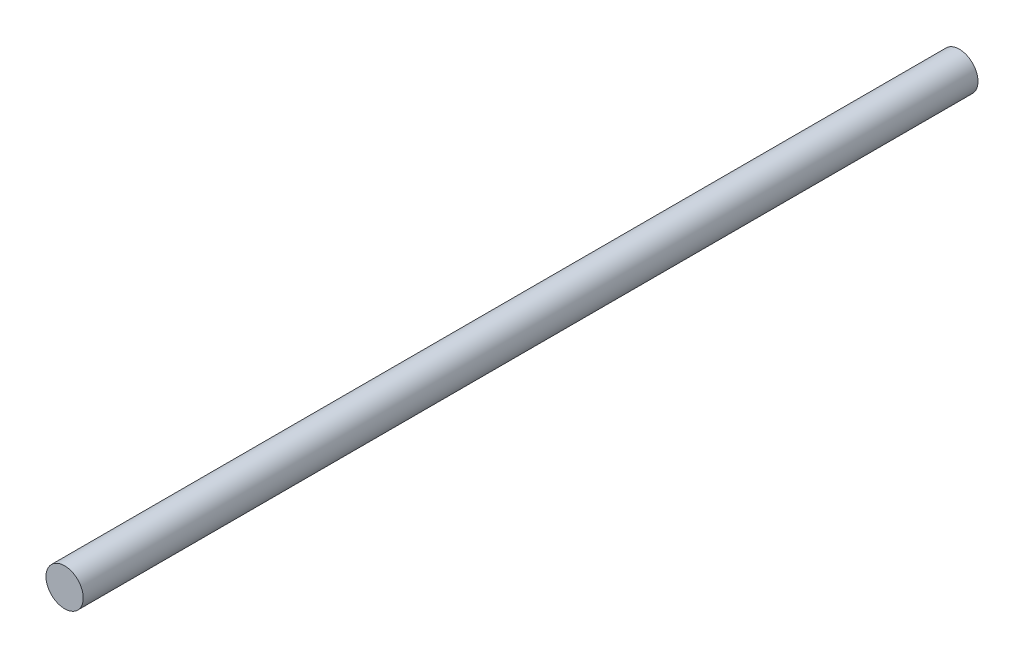
SolidWorks part; units mm, degrees
ref_plane "Front Plane" through (0, 0, 0) normal (0, 0, 1) x (1, 0, 0)
ref_plane "Top Plane" through (0, 0, 0) normal (0, 1, 0) x (1, 0, 0)
ref_plane "Right Plane" through (0, 0, 0) normal (1, 0, 0) x (0, 0, -1)
sketch "Sketch1" plane through (0, 0, 0) normal (0, 0, 1) x (1, 0, 0)
  circle A0 centre (0, 0) radius 2.5
  dimension "D1" = 5
extrude "Boss-Extrude1" add sketch "Sketch1" along normal blind 120 contours A0
